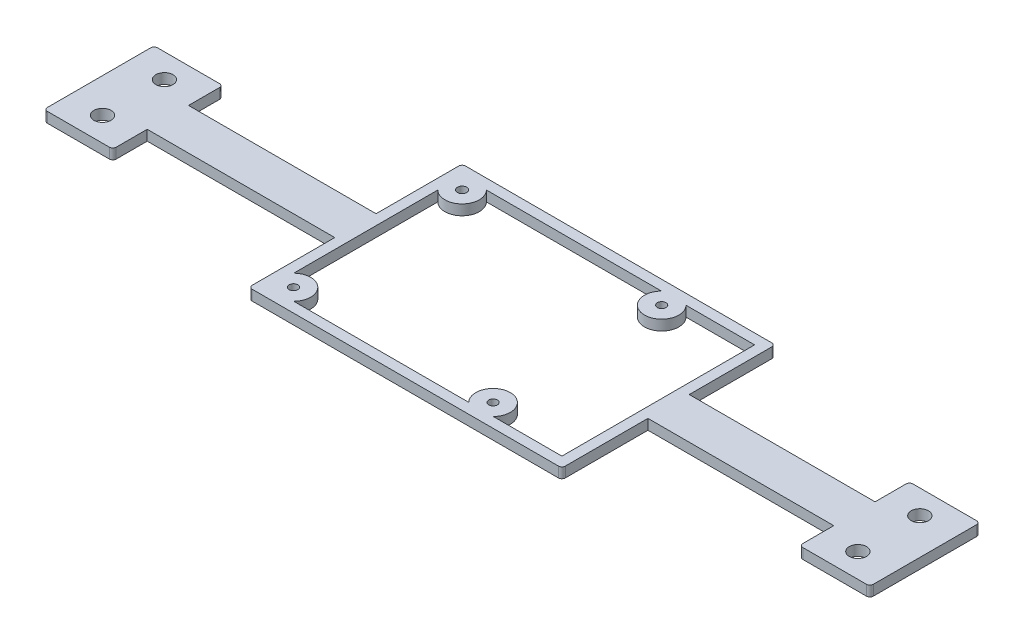
SolidWorks part; units mm, degrees
ref_plane "Front Plane" through (0, 0, 0) normal (0, 0, 1) x (1, 0, 0)
ref_plane "Top Plane" through (0, 0, 0) normal (0, 1, 0) x (1, 0, 0)
ref_plane "Right Plane" through (0, 0, 0) normal (1, 0, 0) x (0, 0, -1)
sketch "Sketch1" plane through (0, 0, 0) normal (0, 1, 0) x (1, 0, 0)
  line L1 (0, 0) -> (91, 0)
  line L2 (0, 0) -> (0, 62)
  line L3 (0, 62) -> (91, 62)
  line L4 (91, 0) -> (91, 62)
extrude "Boss-Extrude3" add sketch "Sketch1" along normal blind 3
sketch "Sketch2" plane through (0, 3, 0) normal (0, 1, 0) x (1, 0, 0)
  line L1 (3, 59) -> (88, 59)
  line L2 (3, 59) -> (3, 3)
  line L3 (3, 3) -> (88, 3)
  line L4 (88, 59) -> (88, 3)
extrude "Cut-Extrude1" cut sketch "Sketch2" against normal blind 3
sketch "Sketch3" plane through (0, 3, 0) normal (0, 1, 0) x (1, 0, 0)
  circle A0 centre (6.5, 6.5) radius 1.25
  circle A1 centre (6.5, 6.5) radius 5
  circle A2 centre (6.5, 55.5) radius 5
  circle A3 centre (6.5, 55.5) radius 1.35
extrude "Boss-Extrude4" add sketch "Sketch3" against normal blind 3
sketch "Sketch4" plane through (0, 0, 0) normal (-1, 0, 0) x (0, 0, 1)
  line L1 (-37, 0) -> (-25, 0)
  line L2 (-37, 0) -> (-37, 3)
  line L3 (-37, 3) -> (-25, 3)
  line L4 (-25, 0) -> (-25, 3)
extrude "Boss-Extrude5" add sketch "Sketch4" along normal blind 54.5
sketch "Sketch5" plane through (0, 3, 0) normal (0, 1, 0) x (1, 0, 0)
  line L1 (-54.5, 15) -> (-74.5, 15)
  line L2 (-54.5, 15) -> (-54.5, 47)
  line L3 (-54.5, 47) -> (-74.5, 47)
  line L4 (-74.5, 15) -> (-74.5, 47)
  circle A0 centre (-64.5, 40) radius 2.5
  circle A1 centre (-64.5, 22) radius 2.5
extrude "Boss-Extrude6" add sketch "Sketch5" against normal blind 3
sketch "Sketch6" plane through (91, 0, 0) normal (1, 0, 0) x (0, 0, -1)
  line L1 (37, 3) -> (25, 3)
  line L2 (37, 3) -> (37, 0)
  line L3 (37, 0) -> (25, 0)
  line L4 (25, 3) -> (25, 0)
extrude "Boss-Extrude7" add sketch "Sketch6" along normal blind 54.5
sketch "Sketch7" plane through (0, 3, 0) normal (0, 1, 0) x (1, 0, 0)
  circle A0 centre (64.5, 55.5) radius 1.25
  circle A1 centre (64.5, 6.5) radius 1.25
  circle A6 centre (64.5, 55.5) radius 5
  circle A7 centre (64.5, 6.5) radius 5
extrude "Boss-Extrude8" add sketch "Sketch7" against normal blind 3
sketch "Sketch8" plane through (0, 3, 0) normal (0, 1, 0) x (1, 0, 0)
  line L1 (145, 47) -> (165.5, 47)
  line L2 (145, 47) -> (145, 15)
  line L3 (145, 15) -> (165.5, 15)
  line L4 (165.5, 47) -> (165.5, 15)
  circle A0 centre (155, 40) radius 2.5
  circle A1 centre (155, 22) radius 2.5
extrude "Boss-Extrude9" add sketch "Sketch8" against normal blind 3
fillet "Fillet1" radius 1 12 edges at (91, 1.5, 0) (145, 1.5, -15) (-54.5, 1.5, -15) (0, 1.5, 0) (-74.5, 1.5, -15) (-54.5, 1.5, -47) (-74.5, 1.5, -47) (0, 1.5, -62) (145, 1.5, -47) (165.5, 1.5, -15) (91, 1.5, -62) (165.5, 1.5, -47)
